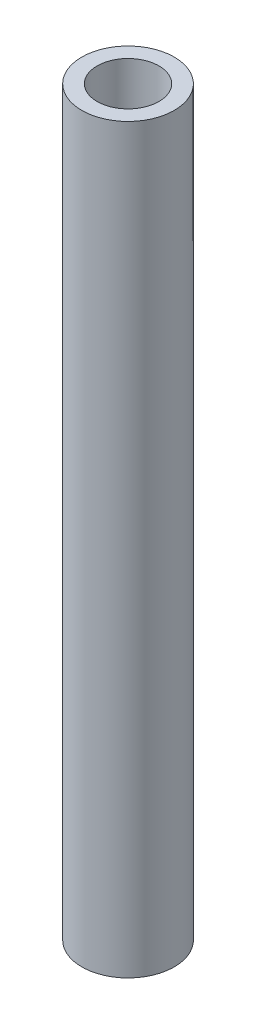
SolidWorks part; units mm, degrees
material "Ceramic Porcelain"
ref_plane "Front Plane" through (0, 0, 0) normal (0, 0, 1) x (1, 0, 0)
ref_plane "Top Plane" through (0, 0, 0) normal (0, 1, 0) x (1, 0, 0)
ref_plane "Right Plane" through (0, 0, 0) normal (1, 0, 0) x (0, 0, -1)
sketch "Sketch1" plane through (0, 0, 0) normal (0, 1, 0) x (1, 0, 0)
  circle A0 centre (0, 0) radius 2.3749
  dimension "D1" = 4.7498
extrude "Boss-Extrude1" add sketch "Sketch1" along normal blind 38.1
sketch "Sketch2" plane through (0, 38.1, 0) normal (0, 1, 0) x (1, 0, 0)
  circle A0 centre (0, 0) radius 1.5875
  dimension "D1" = 3.175
extrude "Cut-Extrude1" cut sketch "Sketch2" against normal through all
